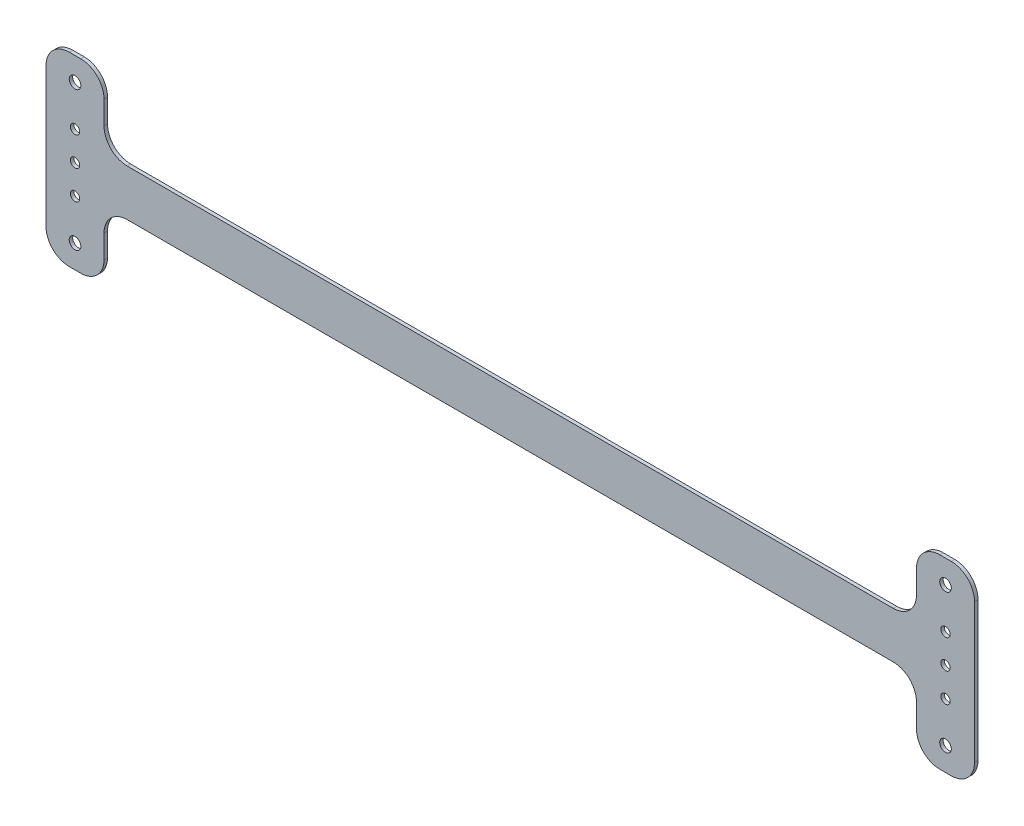
SolidWorks part; units mm, degrees
ref_plane "Front Plane" through (0, 0, 0) normal (0, 0, 1) x (1, 0, 0)
ref_plane "Top Plane" through (0, 0, 0) normal (0, 1, 0) x (1, 0, 0)
ref_plane "Right Plane" through (0, 0, 0) normal (1, 0, 0) x (0, 0, -1)
sketch "Sketch1" plane through (0, 0, 0) normal (0, 0, 1) x (1, 0, 0)
  line L0 (350, 40) -> (350, 0) construction
  line L1 (0, 0) -> (700, 0)
  line L2 (0, 0) -> (0, 40)
  line L3 (0, 40) -> (700, 40)
  line L4 (700, 0) -> (700, 40)
  line L9 (0, 100) -> (-50, 100)
  line L10 (0, 100) -> (0, -60)
  line L11 (0, -60) -> (-50, -60)
  line L12 (-50, 100) -> (-50, -60)
  line L13 (-25, 100) -> (-25, -60) construction
  line L14 (-50, 20) -> (750, 20) construction
  line L16 (725, 100) -> (725, -60) construction
  line L17 (750, 100) -> (750, -60)
  line L18 (700, -60) -> (750, -60)
  line L19 (700, 100) -> (700, -60)
  line L20 (700, 100) -> (750, 100)
  circle A0 centre (-25, 80) radius 5
  circle A3 centre (725, 80) radius 5
  circle A4 centre (725, -40) radius 5
  circle A5 centre (-25, -40) radius 5
  dimension "D6" = 10
  dimension "D7" = 20
  dimension "D1" = 700
  dimension "D2" = 40
  dimension "D3" = 60
  dimension "D4" = 160
  dimension "D5" = 50
  dimension "D8" = 60
extrude "Boss-Extrude1" add sketch "Sketch1" along normal blind 3
fillet "Fillet1" radius 20 12 edges at (0, 0, 1.5) (0, -60, 1.5) (-50, -60, 1.5) (-50, 100, 1.5) (0, 100, 1.5) (0, 40, 1.5) (700, 40, 1.5) (700, 100, 1.5) (750, 100, 1.5) (750, -60, 1.5) (700, -60, 1.5) (700, 0, 1.5)
sketch "Sketch2" plane through (0, 0, 3) normal (0, 0, 1) x (1, 0, 0)
  line L0 (-25, 45) -> (-25, -5) construction
  line L1 (-25, 45) -> (-25, -5) construction
  line L2 (-21, 45) -> (-21, -5)
  line L3 (-29, 45) -> (-29, -5)
  line L4 (-50, 80) -> (-50, -40) construction
  line L6 (-25, 80) -> (-25, -40) construction
  line L7 (350, 40) -> (350, 0) construction
  line L10 (725, 45) -> (725, -5) construction
  line L11 (725, 45) -> (725, -5) construction
  line L12 (721, 45) -> (721, -5)
  line L13 (729, 45) -> (729, -5)
  arc A0 (-21, 45) -> (-29, 45) centre (-25, 45) ccw
  arc A1 (-29, -5) -> (-21, -5) centre (-25, -5) ccw
  circle A2 centre (-25, 45) radius 4
  circle A3 centre (-25, -5) radius 4
  circle A4 centre (-25, 20) radius 4
  circle A5 centre (725, 20) radius 4
  circle A6 centre (725, -5) radius 4
  circle A7 centre (725, 45) radius 4
  arc A8 (721, 45) -> (729, 45) centre (725, 45) cw
  arc A9 (729, -5) -> (721, -5) centre (725, -5) cw
  circle A13 centre (-25, -40) radius 5 construction
  circle A14 centre (-25, 80) radius 5 construction
  point P4 (-25, 20)
  point P35 (725, 20)
  point P44 (-50, 20)
  dimension "D2" = 4
  dimension "D1" = 50
extrude "Cut-Extrude1" cut sketch "Sketch2" against normal through all contours A4 | A3 | A2 | A7 | A5 | A6
